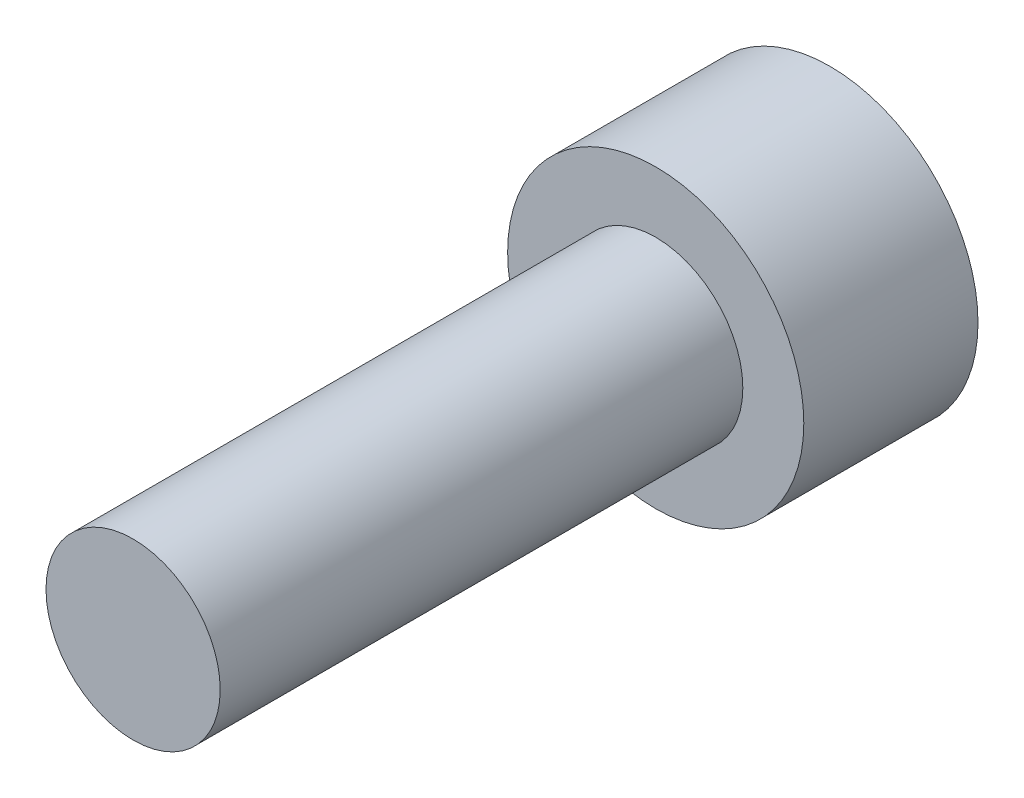
SolidWorks part; units mm, degrees
ref_plane "正面" through (0, 0, 0) normal (0, 0, 1) x (1, 0, 0)
ref_plane "平面" through (0, 0, 0) normal (0, 1, 0) x (1, 0, 0)
ref_plane "右側面" through (0, 0, 0) normal (1, 0, 0) x (0, 0, -1)
sketch "ｽｹｯﾁ1" plane through (0, 0, 0) normal (0, 0, 1) x (1, 0, 0)
  circle A0 centre (0, 0) radius 4.25
  dimension "D1" = 8.5
extrude "ﾎﾞｽ - 押し出し1" add sketch "ｽｹｯﾁ1" along normal blind 5
sketch "ｽｹｯﾁ2" plane through (0, 0, 5) normal (0, 0, 1) x (1, 0, 0)
  circle A0 centre (0, 0) radius 2.5
  dimension "D1" = 5
extrude "ﾎﾞｽ - 押し出し2" add sketch "ｽｹｯﾁ2" along normal blind 15
cosmetic thread "ねじ山1" parameters "D2"=3
sketch "ｽｹｯﾁ3" plane through (0, 0, 0) normal (0, 0, -1) x (-1, 0, 0)
  line L1 (2.4812, -1.1109) -> (2.2027, 1.5934)
  line L2 (2.2027, 1.5934) -> (-0.2785, 2.7043)
  line L3 (-0.2785, 2.7043) -> (-2.4812, 1.1109)
  line L4 (-2.4812, 1.1109) -> (-2.2027, -1.5934)
  line L5 (-2.2027, -1.5934) -> (0.2785, -2.7043)
  line L6 (0.2785, -2.7043) -> (2.4812, -1.1109)
  circle A0 centre (0, 0) radius 2.3544 construction
extrude "ｶｯﾄ - 押し出し1" cut sketch "ｽｹｯﾁ3" against normal blind 2
